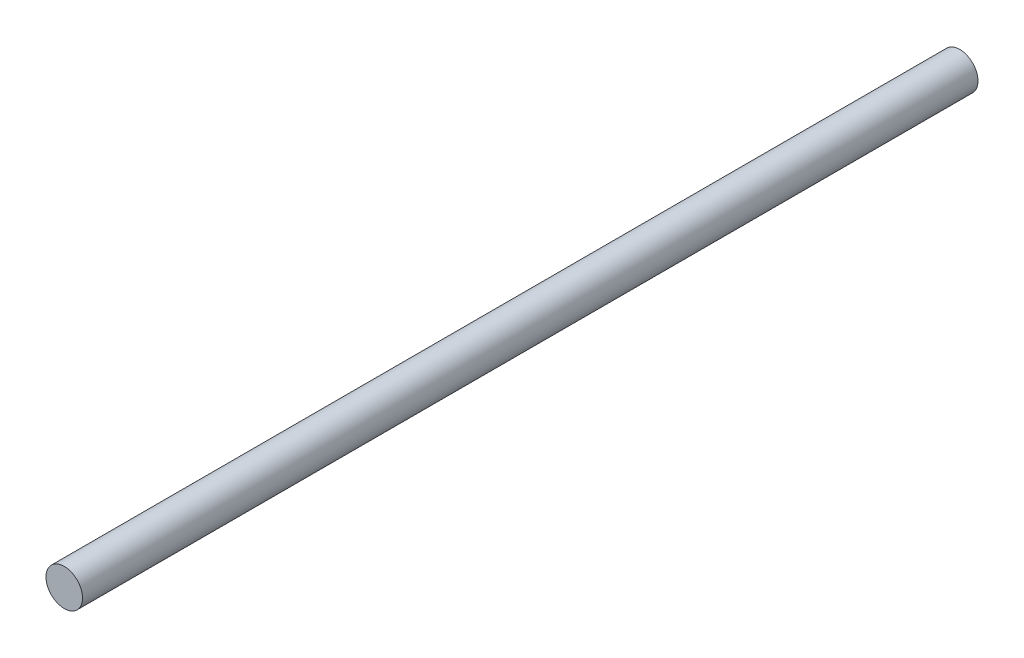
SolidWorks part; units mm, degrees
ref_plane "Plan de face" through (0, 0, 0) normal (0, 0, 1) x (1, 0, 0)
ref_plane "Plan de dessus" through (0, 0, 0) normal (0, 1, 0) x (1, 0, 0)
ref_plane "Plan de droite" through (0, 0, 0) normal (1, 0, 0) x (0, 0, -1)
sketch "Esquisse1" plane through (0, 0, 0) normal (0, 0, 1) x (1, 0, 0)
  circle A0 centre (0, 0) radius 1
  dimension "D1" = 2
extrude "Boss.-Extru.1" add sketch "Esquisse1" along normal blind 49
